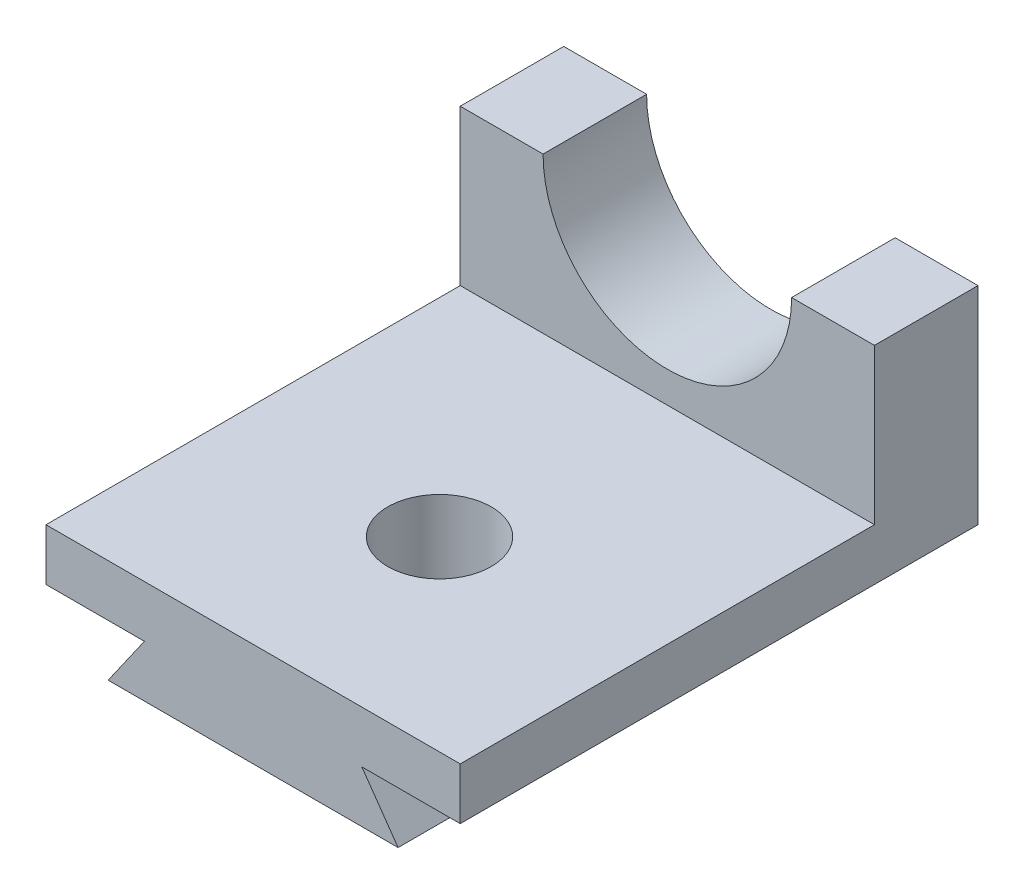
SolidWorks part; units mm, degrees
ref_plane "前视基准面" through (0, 0, 0) normal (0, 0, 1) x (1, 0, 0)
ref_plane "上视基准面" through (0, 0, 0) normal (0, 1, 0) x (1, 0, 0)
ref_plane "右视基准面" through (0, 0, 0) normal (1, 0, 0) x (0, 0, -1)
other "Configuration Table"
sketch "草图1" plane through (0, 0, 0) normal (0, 0, 1) x (1, 0, 0)
  line L0 (-308.4772, 0) -> (15115.3838, 0) construction
  line L1 (0, -308.4772) -> (0, 15115.3838) construction
  line L2 (-20, 0) -> (20, 0)
  line L3 (-14, -10) -> (14, -10)
  line L4 (14, -10) -> (10.5, -5)
  line L6 (-14, -10) -> (-10.5, -5)
  line L8 (20, 0) -> (20, -5)
  line L9 (20, -5) -> (10.5, -5)
  line L10 (-20, 0) -> (-20, -5)
  line L11 (-20, -5) -> (-10.5, -5)
  point P8 (0, 0)
  point P11 (0, -10)
  point P15 (0, 0)
  dimension "D1" = 28
  dimension "D2" = 21
  dimension "D3" = 5
  dimension "D4" = 5
  dimension "D5" = 40
extrude "凸台-拉伸1" add sketch "草图1" along normal blind 50
sketch "草图2" plane through (0, 0, 0) normal (0, 1, 0) x (1, 0, 0)
  line L0 (20, -50) -> (20, 0) construction
  line L1 (-20, 0) -> (20, 0)
  line L2 (-20, 0) -> (-20, -10)
  line L3 (-20, -10) -> (20, -10)
  line L4 (20, 0) -> (20, -10)
  line L5 (0, -1000) -> (0, 49000) construction
  line L6 (20, -50) -> (-20, -50) construction
  circle A0 centre (0, -32) radius 5
  dimension "D4" = 10
  dimension "D1" = 10
  dimension "D2" = 40
  dimension "D3" = 18
extrude "切除-拉伸1" cut sketch "草图2" against normal through all contours A0
sketch "草图3" plane through (0, 0, 0) normal (0, 1, 0) x (1, 0, 0)
  line L0 (20, -50) -> (20, 0) construction
  line L1 (-20, 0) -> (20, 0)
  line L2 (-20, 0) -> (-20, -10)
  line L3 (-20, -10) -> (20, -10)
  line L4 (20, 0) -> (20, -10)
  dimension "D1" = 10
extrude "凸台-拉伸3" add sketch "草图3" along normal blind 15
sketch "草图4" plane through (0, 0, 10) normal (0, 0, 1) x (1, 0, 0)
  line L0 (-20, 15) -> (20, 15) construction
  line L1 (-12, 15) -> (12, 15)
  arc A0 (-12, 15) -> (12, 15) centre (0, 15) ccw
  dimension "D1" = 24
extrude "切除-拉伸2" cut sketch "草图4" against normal through all
